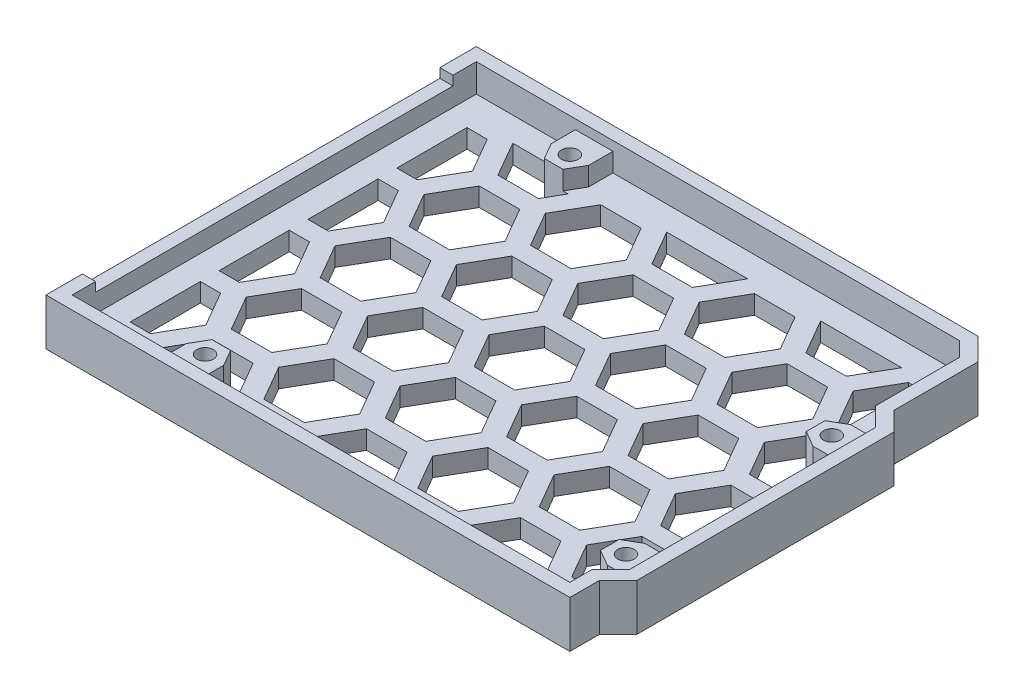
SolidWorks part; units mm, degrees
material "ABS PC"
ref_plane "Front Plane" through (0, 0, 0) normal (0, 0, 1) x (1, 0, 0)
ref_plane "Top Plane" through (0, 0, 0) normal (0, 1, 0) x (1, 0, 0)
ref_plane "Right Plane" through (0, 0, 0) normal (1, 0, 0) x (0, 0, -1)
sketch "Sketch1" plane through (0, 0, 0) normal (0, 1, 0) x (1, 0, 0)
  line L0 (0, 0) -> (64.516, 0) construction
  line L1 (64.516, 0) -> (66.04, -1.524) construction
  line L2 (66.04, -1.524) -> (66.04, -12.954) construction
  line L3 (66.04, -12.954) -> (68.58, -15.494) construction
  line L4 (68.58, -15.494) -> (68.58, -48.26) construction
  line L5 (68.58, -48.26) -> (66.04, -50.8) construction
  line L6 (66.04, -50.8) -> (66.04, -53.34) construction
  line L7 (66.04, -53.34) -> (0, -53.34) construction
  line L8 (0, -53.34) -> (0, 0) construction
  line L9 (-6.35, -9.525) -> (9.525, -9.525) construction
  line L10 (9.525, -9.525) -> (9.525, -20.955) construction
  line L11 (9.525, -20.955) -> (-6.35, -20.955) construction
  line L12 (-6.35, -20.955) -> (-6.35, -9.525) construction
  line L13 (11.43, -50.8) -> (-1.905, -50.8) construction
  line L14 (-1.905, -50.8) -> (-1.905, -41.275) construction
  line L15 (-1.905, -41.275) -> (11.43, -41.275) construction
  line L16 (11.43, -41.275) -> (11.43, -50.8) construction
  line L17 (-2.54, 2.54) -> (65.5681, 2.54)
  line L18 (65.5681, 2.54) -> (68.58, -0.4719)
  line L19 (68.58, -0.4719) -> (68.58, -11.9019)
  line L20 (68.58, -11.9019) -> (71.12, -14.4419)
  line L21 (71.12, -14.4419) -> (71.12, -49.3121)
  line L22 (71.12, -49.3121) -> (68.58, -51.8521)
  line L23 (68.58, -51.8521) -> (68.58, -55.88)
  line L24 (68.58, -55.88) -> (-2.54, -55.88)
  line L25 (-2.54, -55.88) -> (-2.54, 2.54)
  circle A0 centre (15.24, -2.54) radius 1.5875 construction
  circle A1 centre (66.04, -17.78) radius 1.5875 construction
  circle A2 centre (66.04, -45.72) radius 1.5875 construction
  circle A3 centre (13.97, -50.8) radius 1.5875 construction
  dimension "D23" = 3.175
  dimension "D1" = 66.04
  dimension "D2" = 68.58
  dimension "D3" = 2.54
  dimension "D4" = 2.54
  dimension "D5" = 53.34
  dimension "D6" = 51.816
  dimension "D7" = 64.516
  dimension "D8" = 37.846
  dimension "D9" = 12.065
  dimension "D10" = 1.905
  dimension "D11" = 11.43
  dimension "D12" = 32.385
  dimension "D13" = 9.525
  dimension "D14" = 6.35
  dimension "D15" = 43.815
  dimension "D16" = 13.97
  dimension "D17" = 2.54
  dimension "D18" = 50.8
  dimension "D19" = 15.24
  dimension "D20" = 7.62
  dimension "D21" = 66.04
  dimension "D22" = 35.56
  dimension "D24" = 2.54
  dimension "D25" = 2.54
  dimension "D26" = 2.54
  dimension "D27" = 2.54
  dimension "D28" = 2.54
  dimension "D29" = 2.54
  dimension "D30" = 2.54
  dimension "D31" = 2.54
  dimension "D32" = 2.54
extrude "Boss-Extrude1" add sketch "Sketch1" along normal blind 2.54
sketch "Sketch2" plane through (0, 2.54, 0) normal (0, 1, 0) x (1, 0, 0)
  line L0 (2.54, -2.54) -> (63.5, -2.54) construction
  line L1 (66.04, -12.954) -> (68.58, -15.494) construction
  line L2 (63.5, -2.54) -> (63.5, -14.0061) construction
  line L3 (63.5, -14.0061) -> (66.04, -16.5461) construction
  line L4 (66.04, -16.5461) -> (66.04, -47.2079) construction
  line L5 (66.04, -47.2079) -> (63.5, -49.7479) construction
  line L6 (63.5, -49.7479) -> (63.5, -50.8) construction
  line L7 (63.5, -50.8) -> (2.54, -50.8) construction
  line L8 (2.54, -50.8) -> (2.54, -2.54) construction
  line L9 (0, -53.34) -> (0, 0) construction
  line L10 (0, 0) -> (64.516, 0) construction
  line L11 (66.04, -1.524) -> (66.04, -12.954) construction
  line L12 (23.4372, -8.5725) -> (33.8858, -2.54) construction
  line L13 (68.58, -15.494) -> (68.58, -48.26) construction
  line L14 (68.58, -48.26) -> (66.04, -50.8) construction
  line L15 (66.04, -50.8) -> (66.04, -53.34) construction
  line L16 (66.04, -53.34) -> (0, -53.34) construction
  line L17 (2.54, -8.5725) -> (12.9886, -2.54) construction
  line L18 (5.2896, -3.81) -> (2.54, -3.81)
  line L19 (2.54, -3.81) -> (2.54, -13.335)
  line L21 (2.54, -13.335) -> (5.2896, -13.335)
  line L22 (5.2896, -13.335) -> (8.0393, -8.5725)
  line L23 (8.0393, -8.5725) -> (5.2896, -3.81)
  line L24 (26.1868, -3.81) -> (20.6876, -3.81)
  line L25 (20.6876, -3.81) -> (17.9379, -8.5725)
  line L26 (17.9379, -8.5725) -> (20.6876, -13.335)
  line L27 (20.6876, -13.335) -> (26.1868, -13.335)
  line L28 (26.1868, -13.335) -> (28.9365, -8.5725)
  line L29 (28.9365, -8.5725) -> (26.1868, -3.81)
  line L30 (2.54, -15.875) -> (2.54, -25.4)
  line L31 (2.54, -27.94) -> (2.54, -37.465)
  line L32 (7.4893, -2.54) -> (10.239, -7.3025)
  line L33 (10.239, -7.3025) -> (15.7382, -7.3025)
  line L34 (15.7382, -7.3025) -> (18.4879, -2.54)
  line L35 (2.54, -40.005) -> (2.54, -49.53)
  line L36 (2.54, -8.5725) -> (23.4372, -8.5725) construction
  line L37 (23.4372, -8.5725) -> (12.9886, -2.54) construction
  line L38 (33.8858, -2.54) -> (44.3344, -8.5725) construction
  line L39 (15.7382, -9.8425) -> (10.239, -9.8425)
  line L40 (10.239, -9.8425) -> (7.4893, -14.605)
  line L41 (7.4893, -14.605) -> (10.239, -19.3675)
  line L42 (10.239, -19.3675) -> (15.7382, -19.3675)
  line L43 (15.7382, -19.3675) -> (18.4879, -14.605)
  line L44 (18.4879, -14.605) -> (15.7382, -9.8425)
  line L45 (7.4893, -50.8) -> (18.4879, -50.8)
  line L46 (28.3865, -50.8) -> (39.3851, -50.8)
  line L47 (28.3865, -2.54) -> (31.1362, -7.3025)
  line L48 (31.1362, -7.3025) -> (36.6354, -7.3025)
  line L49 (36.6354, -7.3025) -> (39.3851, -2.54)
  line L50 (49.2837, -50.8) -> (60.2822, -50.8)
  line L51 (47.084, -3.81) -> (41.5848, -3.81)
  line L52 (41.5848, -3.81) -> (38.8351, -8.5725)
  line L53 (38.8351, -8.5725) -> (41.5848, -13.335)
  line L54 (41.5848, -13.335) -> (47.084, -13.335)
  line L55 (47.084, -13.335) -> (49.8336, -8.5725)
  line L56 (49.8336, -8.5725) -> (47.084, -3.81)
  line L57 (63.7179, -49.53) -> (66.04, -47.2079)
  line L58 (66.04, -47.2079) -> (66.04, -40.005)
  line L59 (49.2837, -2.54) -> (52.0334, -7.3025)
  line L60 (52.0334, -7.3025) -> (57.5326, -7.3025)
  line L61 (57.5326, -7.3025) -> (60.2822, -2.54)
  line L62 (66.04, -37.465) -> (66.04, -27.94)
  line L63 (36.6354, -9.8425) -> (31.1362, -9.8425)
  line L64 (31.1362, -9.8425) -> (28.3865, -14.605)
  line L65 (28.3865, -14.605) -> (31.1362, -19.3675)
  line L66 (31.1362, -19.3675) -> (36.6354, -19.3675)
  line L67 (36.6354, -19.3675) -> (39.3851, -14.605)
  line L68 (39.3851, -14.605) -> (36.6354, -9.8425)
  line L69 (63.5, -3.81) -> (62.4819, -3.81)
  line L70 (62.4819, -3.81) -> (59.7323, -8.5725)
  line L71 (59.7323, -8.5725) -> (62.4819, -13.335)
  line L72 (62.4819, -13.335) -> (63.5, -13.335)
  line L73 (66.04, -25.4) -> (66.04, -16.5461)
  line L74 (66.04, -16.5461) -> (65.3689, -15.875)
  line L75 (57.5326, -9.8425) -> (52.0334, -9.8425)
  line L76 (52.0334, -9.8425) -> (49.2837, -14.605)
  line L77 (49.2837, -14.605) -> (52.0334, -19.3675)
  line L78 (52.0334, -19.3675) -> (57.5326, -19.3675)
  line L79 (57.5326, -19.3675) -> (60.2822, -14.605)
  line L80 (60.2822, -14.605) -> (57.5326, -9.8425)
  line L81 (23.4372, -8.5725) -> (44.3344, -8.5725) construction
  line L82 (44.3344, -8.5725) -> (65.2316, -8.5725) construction
  line L83 (44.3344, -8.5725) -> (54.783, -2.54) construction
  line L84 (54.783, -2.54) -> (65.2316, -8.5725) construction
  line L85 (2.54, -8.5725) -> (12.9886, -14.605) construction
  line L86 (12.9886, -14.605) -> (23.4372, -8.5725) construction
  line L87 (23.4372, -8.5725) -> (33.8858, -14.605) construction
  line L88 (33.8858, -14.605) -> (44.3344, -8.5725) construction
  line L89 (44.3344, -8.5725) -> (54.783, -14.605) construction
  line L90 (54.783, -14.605) -> (65.2316, -8.5725) construction
  line L91 (12.9886, -14.605) -> (2.54, -20.6375) construction
  line L92 (5.2896, -15.875) -> (2.54, -15.875)
  line L93 (63.5, -13.335) -> (63.5, -3.81)
  line L94 (60.2822, -2.54) -> (49.2837, -2.54)
  line L95 (2.54, -25.4) -> (5.2896, -25.4)
  line L96 (5.2896, -25.4) -> (8.0393, -20.6375)
  line L97 (8.0393, -20.6375) -> (5.2896, -15.875)
  line L98 (26.1868, -15.875) -> (20.6876, -15.875)
  line L99 (20.6876, -15.875) -> (17.9379, -20.6375)
  line L100 (17.9379, -20.6375) -> (20.6876, -25.4)
  line L101 (20.6876, -25.4) -> (26.1868, -25.4)
  line L102 (26.1868, -25.4) -> (28.9365, -20.6375)
  line L103 (28.9365, -20.6375) -> (26.1868, -15.875)
  line L104 (65.3689, -15.875) -> (62.4819, -15.875)
  line L105 (62.4819, -15.875) -> (59.7323, -20.6375)
  line L106 (59.7323, -20.6375) -> (62.4819, -25.4)
  line L107 (62.4819, -25.4) -> (66.04, -25.4)
  line L108 (39.3851, -2.54) -> (28.3865, -2.54)
  line L109 (18.4879, -2.54) -> (7.4893, -2.54)
  line L110 (36.6354, -33.9725) -> (31.1362, -33.9725)
  line L111 (31.1362, -33.9725) -> (28.3865, -38.735)
  line L112 (28.3865, -38.735) -> (31.1362, -43.4975)
  line L113 (31.1362, -43.4975) -> (36.6354, -43.4975)
  line L114 (36.6354, -43.4975) -> (39.3851, -38.735)
  line L115 (39.3851, -38.735) -> (36.6354, -33.9725)
  line L116 (15.7382, -21.9075) -> (10.239, -21.9075)
  line L117 (10.239, -21.9075) -> (7.4893, -26.67)
  line L118 (7.4893, -26.67) -> (10.239, -31.4325)
  line L119 (10.239, -31.4325) -> (15.7382, -31.4325)
  line L120 (15.7382, -31.4325) -> (18.4879, -26.67)
  line L121 (18.4879, -26.67) -> (15.7382, -21.9075)
  line L122 (47.084, -15.875) -> (41.5848, -15.875)
  line L123 (41.5848, -15.875) -> (38.8351, -20.6375)
  line L124 (38.8351, -20.6375) -> (41.5848, -25.4)
  line L125 (41.5848, -25.4) -> (47.084, -25.4)
  line L126 (47.084, -25.4) -> (49.8336, -20.6375)
  line L127 (49.8336, -20.6375) -> (47.084, -15.875)
  line L128 (5.2896, -27.94) -> (2.54, -27.94)
  line L131 (2.54, -37.465) -> (5.2896, -37.465)
  line L132 (5.2896, -37.465) -> (8.0393, -32.7025)
  line L133 (8.0393, -32.7025) -> (5.2896, -27.94)
  line L134 (26.1868, -27.94) -> (20.6876, -27.94)
  line L135 (20.6876, -27.94) -> (17.9379, -32.7025)
  line L136 (17.9379, -32.7025) -> (20.6876, -37.465)
  line L137 (20.6876, -37.465) -> (26.1868, -37.465)
  line L138 (26.1868, -37.465) -> (28.9365, -32.7025)
  line L139 (28.9365, -32.7025) -> (26.1868, -27.94)
  line L140 (47.084, -40.005) -> (41.5848, -40.005)
  line L141 (41.5848, -40.005) -> (38.8351, -44.7675)
  line L142 (38.8351, -44.7675) -> (41.5848, -49.53)
  line L143 (41.5848, -49.53) -> (47.084, -49.53)
  line L144 (47.084, -49.53) -> (49.8336, -44.7675)
  line L145 (49.8336, -44.7675) -> (47.084, -40.005)
  line L146 (52.0334, -21.9075) -> (49.2837, -26.67)
  line L147 (49.2837, -26.67) -> (52.0334, -31.4325)
  line L148 (52.0334, -31.4325) -> (57.5326, -31.4325)
  line L149 (57.5326, -31.4325) -> (60.2822, -26.67)
  line L150 (60.2822, -26.67) -> (57.5326, -21.9075)
  line L151 (57.5326, -21.9075) -> (52.0334, -21.9075)
  line L152 (66.04, -27.94) -> (62.4819, -27.94)
  line L153 (62.4819, -27.94) -> (59.7323, -32.7025)
  line L154 (59.7323, -32.7025) -> (62.4819, -37.465)
  line L155 (62.4819, -37.465) -> (66.04, -37.465)
  line L158 (15.7382, -33.9725) -> (10.239, -33.9725)
  line L159 (10.239, -33.9725) -> (7.4893, -38.735)
  line L160 (7.4893, -38.735) -> (10.239, -43.4975)
  line L161 (10.239, -43.4975) -> (15.7382, -43.4975)
  line L162 (15.7382, -43.4975) -> (18.4879, -38.735)
  line L163 (18.4879, -38.735) -> (15.7382, -33.9725)
  line L164 (5.2896, -40.005) -> (2.54, -40.005)
  line L167 (2.54, -49.53) -> (5.2896, -49.53)
  line L168 (5.2896, -49.53) -> (8.0393, -44.7675)
  line L169 (8.0393, -44.7675) -> (5.2896, -40.005)
  line L170 (26.1868, -40.005) -> (20.6876, -40.005)
  line L171 (20.6876, -40.005) -> (17.9379, -44.7675)
  line L172 (17.9379, -44.7675) -> (20.6876, -49.53)
  line L173 (20.6876, -49.53) -> (26.1868, -49.53)
  line L174 (26.1868, -49.53) -> (28.9365, -44.7675)
  line L175 (28.9365, -44.7675) -> (26.1868, -40.005)
  line L176 (47.084, -27.94) -> (41.5848, -27.94)
  line L177 (41.5848, -27.94) -> (38.8351, -32.7025)
  line L178 (38.8351, -32.7025) -> (41.5848, -37.465)
  line L179 (41.5848, -37.465) -> (47.084, -37.465)
  line L180 (47.084, -37.465) -> (49.8336, -32.7025)
  line L181 (49.8336, -32.7025) -> (47.084, -27.94)
  line L182 (36.6354, -21.9075) -> (31.1362, -21.9075)
  line L183 (31.1362, -21.9075) -> (28.3865, -26.67)
  line L184 (28.3865, -26.67) -> (31.1362, -31.4325)
  line L185 (31.1362, -31.4325) -> (36.6354, -31.4325)
  line L186 (36.6354, -31.4325) -> (39.3851, -26.67)
  line L187 (39.3851, -26.67) -> (36.6354, -21.9075)
  line L188 (57.5326, -33.9725) -> (52.0334, -33.9725)
  line L189 (52.0334, -33.9725) -> (49.2837, -38.735)
  line L190 (49.2837, -38.735) -> (52.0334, -43.4975)
  line L191 (52.0334, -43.4975) -> (57.5326, -43.4975)
  line L192 (57.5326, -43.4975) -> (60.2822, -38.735)
  line L193 (60.2822, -38.735) -> (57.5326, -33.9725)
  line L194 (66.04, -40.005) -> (62.4819, -40.005)
  line L195 (62.4819, -40.005) -> (59.7323, -44.7675)
  line L196 (59.7323, -44.7675) -> (62.4819, -49.53)
  line L197 (62.4819, -49.53) -> (63.7179, -49.53)
  line L200 (2.54, -20.6375) -> (12.9886, -26.67) construction
  line L201 (12.9886, -26.67) -> (2.54, -32.7025) construction
  line L202 (2.54, -32.7025) -> (12.9886, -38.735) construction
  line L203 (12.9886, -38.735) -> (2.54, -44.7675) construction
  line L204 (23.4372, -44.7675) -> (12.9886, -38.735) construction
  line L205 (12.9886, -38.735) -> (23.4372, -32.7025) construction
  line L206 (23.4372, -32.7025) -> (12.9886, -26.67) construction
  line L207 (12.9886, -26.67) -> (23.4372, -20.6375) construction
  line L208 (23.4372, -20.6375) -> (12.9886, -14.605) construction
  line L209 (23.4372, -20.6375) -> (33.8858, -26.67) construction
  line L210 (33.8858, -26.67) -> (23.4372, -32.7025) construction
  line L211 (23.4372, -32.7025) -> (33.8858, -38.735) construction
  line L212 (33.8858, -38.735) -> (23.4372, -44.7675) construction
  line L213 (23.4372, -20.6375) -> (33.8858, -14.605) construction
  line L214 (54.783, -14.605) -> (44.3344, -20.6375) construction
  line L215 (44.3344, -20.6375) -> (33.8858, -26.67) construction
  line L216 (33.8858, -26.67) -> (44.3344, -32.7025) construction
  line L217 (44.3344, -32.7025) -> (54.783, -26.67) construction
  line L218 (54.783, -26.67) -> (44.3344, -20.6375) construction
  line L219 (33.8858, -14.605) -> (44.3344, -20.6375) construction
  line L220 (33.8858, -38.735) -> (44.3344, -44.7675) construction
  line L221 (44.3344, -44.7675) -> (54.783, -38.735) construction
  line L222 (54.783, -38.735) -> (44.3344, -32.7025) construction
  line L223 (44.3344, -32.7025) -> (33.8858, -38.735) construction
  line L224 (54.783, -14.605) -> (65.2316, -20.6375) construction
  line L225 (65.2316, -20.6375) -> (54.783, -26.67) construction
  line L226 (54.783, -26.67) -> (65.2316, -32.7025) construction
  line L227 (65.2316, -32.7025) -> (54.783, -38.735) construction
  line L228 (54.783, -38.735) -> (65.2316, -44.7675) construction
  line L229 (2.54, -44.7675) -> (23.4372, -44.7675) construction
  line L230 (23.4372, -44.7675) -> (44.3344, -44.7675) construction
  line L231 (2.54, -44.7675) -> (12.9886, -50.8) construction
  line L232 (15.7382, -46.0375) -> (10.239, -46.0375)
  line L233 (10.239, -46.0375) -> (7.4893, -50.8)
  line L237 (18.4879, -50.8) -> (15.7382, -46.0375)
  line L238 (36.6354, -46.0375) -> (31.1362, -46.0375)
  line L239 (31.1362, -46.0375) -> (28.3865, -50.8)
  line L243 (39.3851, -50.8) -> (36.6354, -46.0375)
  line L244 (57.5326, -46.0375) -> (52.0334, -46.0375)
  line L245 (52.0334, -46.0375) -> (49.2837, -50.8)
  line L249 (60.2822, -50.8) -> (57.5326, -46.0375)
  line L250 (12.9886, -50.8) -> (23.4372, -44.7675) construction
  line L251 (23.4372, -44.7675) -> (33.8858, -50.8) construction
  line L252 (33.8858, -50.8) -> (44.3344, -44.7675) construction
  line L253 (44.3344, -44.7675) -> (54.783, -50.8) construction
  line L254 (54.783, -50.8) -> (65.2316, -44.7675) construction
  line L256 (-2.9593, -32.7025) -> (-1.5844, -35.0837) [skipped]
  line L257 (-0.2096, -27.94) -> (-1.5844, -30.3212) [skipped]
  line L258 (-0.2096, -40.005) -> (-1.5844, -42.3862) [skipped]
  line L259 (-2.9593, -44.7675) -> (-0.2096, -49.53) [skipped]
  line L260 (8.8642, -53.1812) -> (10.239, -55.5625) [skipped]
  line L261 (12.9886, -55.5625) -> (15.7382, -55.5625) [skipped]
  line L262 (17.113, -53.1812) -> (18.4879, -50.8) [skipped]
  line L263 (29.7613, -53.1812) -> (31.1362, -55.5625) [skipped]
  line L264 (33.8858, -55.5625) -> (36.6354, -55.5625) [skipped]
  line L265 (38.0102, -53.1812) -> (39.3851, -50.8) [skipped]
  line L266 (57.5326, -55.5625) -> (58.9074, -53.1812) [skipped]
  line L267 (52.0334, -55.5625) -> (54.783, -55.5625) [skipped]
  line L268 (49.2837, -50.8) -> (50.6585, -53.1812) [skipped]
  line L269 (70.7308, -44.7675) -> (69.356, -42.3862) [skipped]
  line L270 (67.9812, -49.53) -> (69.356, -47.1487) [skipped]
  line L271 (67.9812, -37.465) -> (69.356, -35.0837) [skipped]
  line L272 (69.356, -18.2563) -> (67.9812, -15.875) [skipped]
  line L273 (67.9812, -25.4) -> (69.356, -23.0187) [skipped]
  line L274 (69.356, -30.3212) -> (67.9812, -27.94) [skipped]
  line L275 (67.9812, -13.335) -> (70.7308, -8.5725) [skipped]
  line L276 (69.356, -6.1913) -> (67.9812, -3.81) [skipped]
  line L277 (60.2822, -2.54) -> (58.9074, -0.1588) [skipped]
  line L278 (54.783, 2.2225) -> (52.0334, 2.2225) [skipped]
  line L279 (50.6585, -0.1588) -> (49.2837, -2.54) [skipped]
  line L280 (29.7613, -0.1588) -> (28.3865, -2.54) [skipped]
  line L281 (36.6354, 2.2225) -> (31.1362, 2.2225) [skipped]
  line L282 (39.3851, -2.54) -> (38.0102, -0.1587) [skipped]
  line L283 (17.113, -0.1587) -> (15.7382, 2.2225) [skipped]
  line L284 (12.9886, 2.2225) -> (10.239, 2.2225) [skipped]
  line L285 (8.8642, -0.1588) -> (7.4893, -2.54) [skipped]
  line L286 (-1.5844, -6.1912) -> (-2.9593, -8.5725) [skipped]
  line L287 (-2.9593, -8.5725) -> (-1.5844, -10.9537) [skipped]
  line L288 (-1.5844, -18.2562) -> (-2.9593, -20.6375) [skipped]
  line L289 (-1.5844, -23.0187) -> (-0.2096, -25.4) [skipped]
  arc A0 (2.54, -13.335) -> (2.54, -3.81) centre (2.54, -8.5725) ccw construction
  circle A1 centre (23.4372, -8.5725) radius 4.7625 construction
  arc A2 (8.2261, -2.54) -> (17.7511, -2.54) centre (12.9886, -2.54) ccw construction
  circle A3 centre (12.9886, -14.605) radius 4.7625 construction
  arc A4 (29.1233, -2.54) -> (38.6483, -2.54) centre (33.8858, -2.54) ccw construction
  circle A5 centre (44.3344, -8.5725) radius 4.7625 construction
  arc A6 (50.0205, -2.54) -> (59.5455, -2.54) centre (54.783, -2.54) ccw construction
  circle A7 centre (33.8858, -14.605) radius 4.7625 construction
  arc A8 (63.5, -4.1359) -> (63.5, -13.0091) centre (65.2316, -8.5725) ccw construction
  circle A9 centre (54.783, -14.605) radius 4.7625 construction
  arc A10 (2.54, -25.4) -> (2.54, -15.875) centre (2.54, -20.6375) ccw construction
  circle A11 centre (23.4372, -20.6375) radius 4.7625 construction
  arc A12 (65.3709, -15.877) -> (66.04, -25.3309) centre (65.2316, -20.6375) ccw construction
  circle A13 centre (33.8858, -38.735) radius 4.7625 construction
  circle A14 centre (12.9886, -26.67) radius 4.7625 construction
  circle A15 centre (44.3344, -20.6375) radius 4.7625 construction
  arc A16 (2.54, -37.465) -> (2.54, -27.94) centre (2.54, -32.7025) ccw construction
  circle A17 centre (23.4372, -32.7025) radius 4.7625 construction
  circle A18 centre (44.3344, -44.7675) radius 4.7625 construction
  circle A19 centre (54.783, -26.67) radius 4.7625 construction
  arc A20 (66.04, -28.0091) -> (66.04, -37.3959) centre (65.2316, -32.7025) ccw construction
  circle A21 centre (12.9886, -38.735) radius 4.7625 construction
  arc A22 (2.54, -49.53) -> (2.54, -40.005) centre (2.54, -44.7675) ccw construction
  circle A23 centre (23.4372, -44.7675) radius 4.7625 construction
  circle A24 centre (44.3344, -32.7025) radius 4.7625 construction
  circle A25 centre (33.8858, -26.67) radius 4.7625 construction
  circle A26 centre (54.783, -38.735) radius 4.7625 construction
  arc A27 (66.04, -40.0741) -> (63.9061, -49.3418) centre (65.2316, -44.7675) ccw construction
  arc A28 (17.7511, -50.8) -> (8.2261, -50.8) centre (12.9886, -50.8) ccw construction
  arc A29 (38.6483, -50.8) -> (29.1233, -50.8) centre (33.8858, -50.8) ccw construction
  arc A30 (59.5455, -50.8) -> (50.0205, -50.8) centre (54.783, -50.8) ccw construction
  dimension "D1" = 2.54
  dimension "D2" = 2.54
  dimension "D3" = 2.54
  dimension "D4" = 2.54
  dimension "D5" = 2.54
  dimension "D6" = 2.54
  dimension "D7" = 2.54
  dimension "D8" = 2.54
  dimension "D9" = 9.525
  dimension "D10" = 2.54
extrude "Cut-Extrude1" cut sketch "Sketch2" against normal through all
sketch "Sketch3" plane through (0, 2.54, 0) normal (0, 1, 0) x (1, 0, 0)
  line L0 (11.43, -50.8) -> (12.7, -48.6003)
  line L1 (7.4893, -50.8) -> (18.4879, -50.8) construction
  line L2 (12.7, -48.6003) -> (15.24, -48.6003)
  line L3 (15.24, -48.6003) -> (16.51, -50.8)
  line L4 (13.97, -50.8) -> (13.97, -48.6003) construction
  line L5 (11.43, -50.8) -> (16.51, -50.8)
  line L6 (63.8403, -46.99) -> (63.8403, -44.45)
  line L7 (63.8403, -44.45) -> (66.04, -43.18)
  line L8 (66.04, -47.2079) -> (66.04, -40.005) construction
  line L9 (63.8403, -46.99) -> (65.373, -47.8749)
  line L10 (65.373, -47.8749) -> (66.04, -47.3075)
  line L11 (66.04, -45.72) -> (63.8403, -45.72) construction
  line L12 (63.7179, -49.53) -> (66.04, -47.2079) construction
  line L13 (66.04, -47.3075) -> (66.04, -43.18)
  line L14 (63.8403, -15.875) -> (63.8403, -19.05)
  line L15 (63.8403, -19.05) -> (66.04, -20.32)
  line L16 (66.04, -25.4) -> (66.04, -16.5461) construction
  line L17 (65.3689, -15.875) -> (62.4819, -15.875) construction
  line L18 (15.24, -2.54) -> (15.24, -4.7397) construction
  line L19 (63.8403, -17.78) -> (66.04, -17.78) construction
  line L20 (12.7, -2.54) -> (13.97, -4.7397)
  line L21 (18.4879, -2.54) -> (7.4893, -2.54) construction
  line L22 (13.97, -4.7397) -> (17.2179, -4.7397)
  line L23 (15.7382, -7.3025) -> (18.4879, -2.54) construction
  line L24 (15.24, -2.54) -> (13.335, -3.6399) construction
  line L25 (66.04, -17.78) -> (64.9401, -19.685) construction
  line L26 (12.7, -2.54) -> (18.4879, -2.54)
  line L27 (18.4879, -2.54) -> (17.2179, -4.7397)
  line L28 (63.8403, -15.875) -> (65.3689, -15.875)
  line L29 (65.3689, -15.875) -> (66.04, -16.5461)
  line L30 (66.04, -16.5461) -> (66.04, -20.32)
  circle A0 centre (66.04, -45.72) radius 1.5875 construction
  dimension "D1" = 2.54
  dimension "D2" = 2.54
  dimension "D3" = 120
  dimension "D4" = 120
  dimension "D5" = 2.54
  dimension "D6" = 2.54
  dimension "D7" = 120
  dimension "D8" = 120
  dimension "D9" = 2.54
  dimension "D10" = 120
  dimension "D11" = 2.54
  dimension "D12" = 120
extrude "Boss-Extrude2" add sketch "Sketch3" against normal up to surface (2.54 mm away) up to face at (54.783, 0, 48.4187)
sketch "Sketch7" plane through (0, 2.54, 0) normal (0, 1, 0) x (1, 0, 0)
  line L0 (11.43, -50.8) -> (12.7, -48.6003)
  line L1 (12.7, -48.6003) -> (15.24, -48.6003)
  line L2 (15.24, -48.6003) -> (16.51, -50.8)
  line L3 (16.51, -50.8) -> (16.51, -55.88)
  line L5 (16.51, -55.88) -> (11.43, -55.88)
  line L6 (11.43, -55.88) -> (11.43, -50.8)
  line L7 (66.04, -43.18) -> (71.12, -43.18)
  line L9 (66.04, -43.18) -> (63.8403, -44.45)
  line L10 (63.8403, -44.45) -> (63.8403, -46.99)
  line L11 (63.8403, -46.99) -> (66.04, -48.26)
  line L12 (66.04, -48.26) -> (71.12, -48.26)
  line L13 (66.04, -20.32) -> (71.12, -20.32)
  line L14 (66.04, -20.32) -> (63.8403, -19.05)
  line L15 (63.8403, -19.05) -> (63.8403, -16.51)
  line L16 (63.8403, -15.875) -> (63.8403, -19.05) construction
  line L17 (63.8403, -16.51) -> (66.04, -15.24)
  line L18 (66.04, -15.24) -> (71.12, -15.24)
  line L19 (65.5681, 2.54) -> (-2.54, 2.54) construction
  line L20 (12.7, -2.54) -> (12.7, 2.54)
  line L22 (12.7, 2.54) -> (17.78, 2.54)
  line L23 (17.78, 2.54) -> (17.78, -2.54)
  line L24 (13.97, -4.7397) -> (16.51, -4.7397)
  line L25 (13.97, -4.7397) -> (17.2179, -4.7397) construction
  line L26 (13.97, -4.7397) -> (12.7, -2.54)
  line L27 (16.51, -4.7397) -> (17.78, -2.54)
  line L28 (71.12, -43.18) -> (71.12, -48.26)
  line L29 (71.12, -15.24) -> (71.12, -20.32)
  line L30 (71.12, -49.3121) -> (71.12, -14.4419) construction
  line L31 (-2.54, -55.88) -> (68.58, -55.88) construction
  dimension "D1" = 120
  dimension "D2" = 120
extrude "Boss-Extrude4" add sketch "Sketch7" along normal blind 2.54
hole_wizard "#4-40 Tapped Hole2" positions "Sketch9" profile "Sketch8" tap size "#4-40" standard "ANSI Inch"
sketch "Sketch9" plane through (0, 5.08, 0) normal (0, 1, 0) x (1, 0, 0)
  point P0 (15.24, -2.54)
  point P3 (66.04, -17.78)
  point P6 (66.04, -45.72)
  point P9 (13.97, -50.8)
sketch "Sketch8" plane through (15.24, 5.08, 2.54) normal (1, 0, 0) x (0, 0, 1)
  line L0 (0, 0) -> (0, 4.4892)
  line L1 (0, 4.4892) -> (1.1303, 3.81)
  line L2 (1.1303, 3.81) -> (1.1303, 0)
  line L5 (1.1303, 0) -> (0, 0)
  line L10 (0, 4.4892) -> (-1.1303, 3.81) construction
  line L11 (0, -6.35) -> (0, 107.95) construction
  dimension "Tap Drill Dia." = 2.2606
  dimension "Tap Drill Depth" = 3.81
  dimension "Drill Angle" = 118
cosmetic thread "Hole Thread5" parameters "D1"=3.81, "D2"=2.8448
cosmetic thread "Hole Thread6" parameters "D1"=3.81, "D2"=2.8448
cosmetic thread "Hole Thread7" parameters "D1"=3.81, "D2"=2.8448
cosmetic thread "Hole Thread8" parameters "D1"=3.81, "D2"=2.8448
sketch "Sketch6" plane through (0, 2.54, 0) normal (0, 1, 0) x (1, 0, 0)
  line L0 (-2.54, -55.88) -> (68.58, -55.88)
  line L1 (68.58, -55.88) -> (68.58, -51.8521)
  line L2 (68.58, -51.8521) -> (71.12, -49.3121)
  line L3 (71.12, -49.3121) -> (71.12, -14.4419)
  line L4 (71.12, -14.4419) -> (68.58, -11.9019)
  line L5 (68.58, -11.9019) -> (68.58, -0.4719)
  line L6 (68.58, -0.4719) -> (65.5681, 2.54)
  line L7 (65.5681, 2.54) -> (-2.54, 2.54)
  line L8 (-2.54, 2.54) -> (-2.54, -2.413)
  line L9 (-2.54, -55.88) -> (-2.54, 2.54) construction
  line L10 (-2.54, -50.927) -> (-0.762, -50.927)
  line L12 (-0.762, -50.927) -> (-0.762, -54.102)
  line L13 (-0.762, -54.102) -> (66.802, -54.102)
  line L14 (66.802, -54.102) -> (66.802, -51.1156)
  line L15 (66.802, -51.1156) -> (69.342, -48.5756)
  line L16 (69.342, -48.5756) -> (69.342, -15.1784)
  line L17 (69.342, -15.1784) -> (66.802, -12.6384)
  line L18 (66.802, -12.6384) -> (66.802, -1.2084)
  line L19 (66.802, -1.2084) -> (64.8316, 0.762)
  line L20 (64.8316, 0.762) -> (-0.762, 0.762)
  line L21 (-0.762, 0.762) -> (-0.762, -2.413)
  line L22 (-0.762, -2.413) -> (-2.54, -2.413)
  line L23 (-2.54, -50.927) -> (-2.54, -55.88)
  line L25 (0, -53.34) -> (0, 0) construction
  line L26 (0, 0) -> (64.516, 0) construction
  line L27 (64.516, 0) -> (66.04, -1.524) construction
  line L28 (66.04, -1.524) -> (66.04, -12.954) construction
  line L30 (66.04, -12.954) -> (68.58, -15.494) construction
  line L31 (68.58, -15.494) -> (68.58, -48.26) construction
  line L32 (68.58, -48.26) -> (66.04, -50.8) construction
  line L33 (66.04, -50.8) -> (66.04, -53.34) construction
  line L34 (66.04, -53.34) -> (0, -53.34) construction
  dimension "D2" = 0.762
  dimension "D3" = 0.762
  dimension "D4" = 0.762
  dimension "D5" = 0.762
  dimension "D6" = 0.762
  dimension "D7" = 0.762
  dimension "D8" = 0.762
  dimension "D9" = 0.762
  dimension "D10" = 0.762
  dimension "D11" = 0.762
  dimension "D12" = 3.175
  dimension "D13" = 3.175
extrude "Boss-Extrude3" add sketch "Sketch6" along normal blind 3.81
sketch "Sketch10" plane through (0, 2.54, 0) normal (0, 1, 0) x (1, 0, 0)
  line L1 (-2.54, -2.413) -> (-0.762, -2.413)
  line L2 (-2.54, -2.413) -> (-2.54, -50.927)
  line L3 (-2.54, -50.927) -> (-0.762, -50.927)
  line L4 (-0.762, -2.413) -> (-0.762, -50.927)
extrude "Boss-Extrude5" add sketch "Sketch10" along normal blind 2.54
